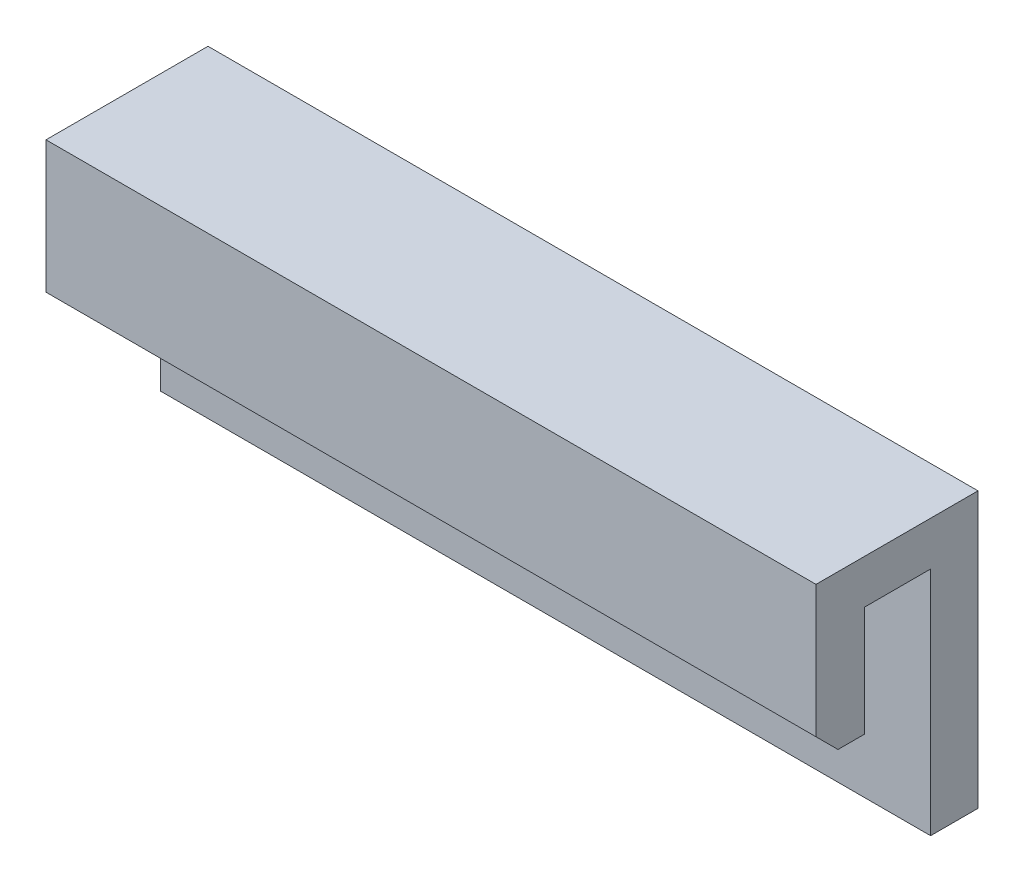
SolidWorks part; units mm, degrees
ref_plane "Front Plane" through (0, 0, 0) normal (0, 0, 1) x (1, 0, 0)
ref_plane "Top Plane" through (0, 0, 0) normal (0, 1, 0) x (1, 0, 0)
ref_plane "Right Plane" through (0, 0, 0) normal (1, 0, 0) x (0, 0, -1)
sketch "Sketch1" plane through (0, 0, 0) normal (1, 0, 0) x (0, 0, -1)
  line L1 (-7.2, 6.0182) -> (7.5273, 6.0182)
  line L2 (-7.2, 6.0182) -> (-7.2, -7.9818)
  line L3 (-7.2, -7.9818) -> (-2.7818, -7.9818)
  line L4 (7.5273, 6.0182) -> (7.5273, -10.3818)
  line L6 (-2.7818, -7.9818) -> (-2.7818, 2.0182)
  line L7 (-2.7818, 2.0182) -> (3.2182, 2.0182)
  line L8 (3.2182, -7.9818) -> (3.2182, 2.0182)
  line L10 (3.2182, -7.9818) -> (3.2182, -18.9818)
  line L11 (3.2182, -18.9818) -> (7.5273, -18.9818)
  line L12 (7.5273, -10.3818) -> (7.5273, -18.9818)
  dimension "D1" = 6
  dimension "D2" = 10
  dimension "D3" = 4
  dimension "D4" = 25
extrude "Boss-Extrude1" add sketch "Sketch1" along normal blind 70
chamfer "Chamfer1" distance 2 angle 45 1 edges at (35, -7.9818, 7.2)
